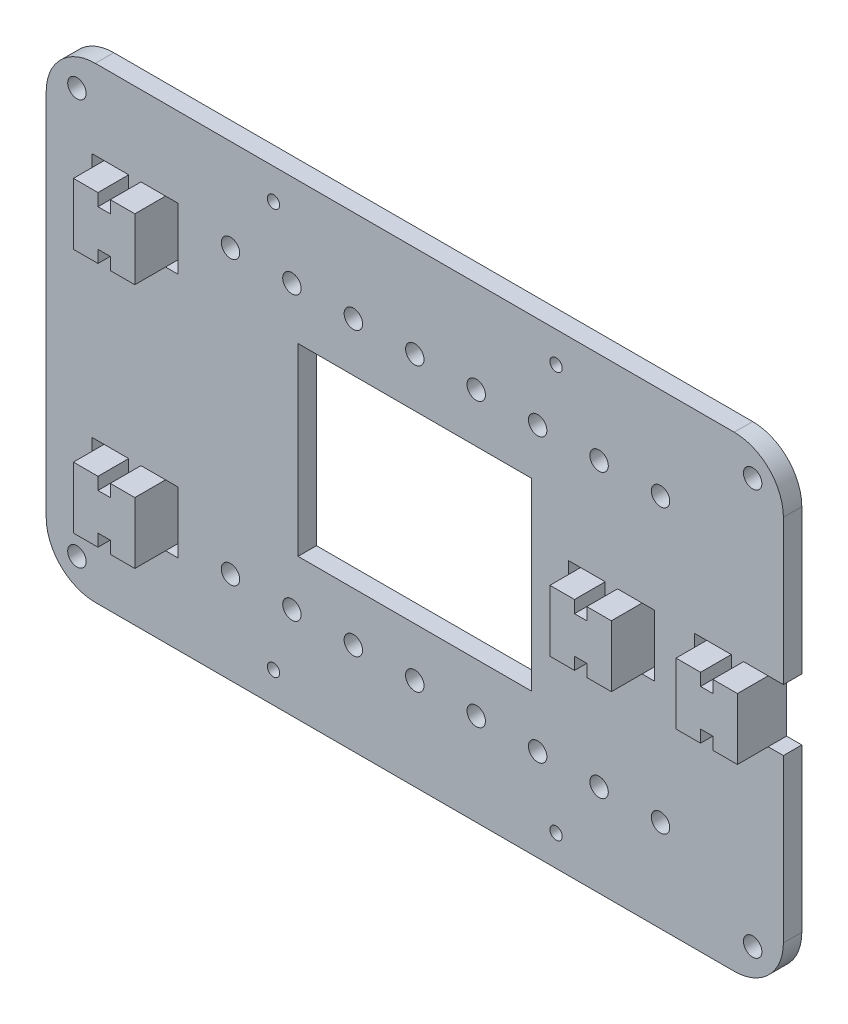
SolidWorks part; units mm, degrees
ref_plane "前视基准面" through (0, 0, 0) normal (0, 0, 1) x (1, 0, 0)
ref_plane "上视基准面" through (0, 0, 0) normal (0, 1, 0) x (1, 0, 0)
ref_plane "右视基准面" through (0, 0, 0) normal (1, 0, 0) x (0, 0, -1)
sketch "草图1" plane through (0, 0, 0) normal (0, 0, 1) x (1, 0, 0)
  line L0 (0, 0) -> (0, 3) construction
  line L1 (-5, 5) -> (-1, 5)
  line L2 (-5, 5) -> (-5, -5)
  line L3 (-5, -5) -> (-1, -5)
  line L4 (5, 5) -> (5, -5)
  line L5 (-5, 5) -> (5, -5) construction
  line L6 (-5, -5) -> (5, 5) construction
  line L7 (-1, 3) -> (1, 3)
  line L8 (-1, 3) -> (-1, 5)
  line L9 (1, 3) -> (1, 5)
  line L10 (0, 0) -> (2.3231, 0) construction
  line L11 (1, -3) -> (1, -5)
  line L12 (-1, -3) -> (1, -3)
  line L13 (-1, -3) -> (-1, -5)
  line L14 (1, 5) -> (5, 5)
  line L15 (1, -5) -> (5, -5)
  point P0 (0, 0)
  point P11 (0, 3)
  dimension "D1" = 10
  dimension "D2" = 10
  dimension "D3" = 2
  dimension "D4" = 2
sketch "草图2" plane through (0, 0, 0) normal (0, 0, 1) x (1, 0, 0)
  line L0 (0, -35) -> (0, 35) construction
  line L1 (-25, 35) -> (25, 35) construction
  line L2 (-25, 35) -> (-25, -35) construction
  line L3 (-25, -35) -> (25, -35) construction
  line L4 (25, 35) -> (25, -35) construction
  line L5 (57.5198, -3.5829) -> (57.5198, 6.4171) construction
  line L6 (-25, 0) -> (25, 0) construction
  line L7 (53.5198, -3.5829) -> (57.5198, -3.5829) construction
  line L8 (53.5198, 6.4171) -> (53.5198, 4.4171) construction
  line L9 (-60, 38) -> (60, 38)
  line L10 (-60, 38) -> (-60, -38)
  line L11 (-60, -38) -> (60, -38)
  line L12 (60, 38) -> (60, -38)
  line L13 (-60, 38) -> (60, -38) construction
  line L14 (-60, -38) -> (60, 38) construction
  line L15 (47.5198, -3.5829) -> (51.5198, -3.5829) construction
  line L16 (57.5198, 6.4171) -> (53.5198, 6.4171) construction
  line L17 (51.5198, -3.5829) -> (51.5198, -1.5829) construction
  line L18 (47.5198, 6.4171) -> (47.5198, -3.5829) construction
  line L19 (51.5198, -1.5829) -> (53.5198, -1.5829) construction
  line L20 (53.5198, -1.5829) -> (53.5198, -3.5829) construction
  line L21 (53.5198, 4.4171) -> (51.5198, 4.4171) construction
  line L22 (51.5198, 6.4171) -> (47.5198, 6.4171) construction
  line L23 (51.5198, 4.4171) -> (51.5198, 6.4171) construction
  line L24 (-5, -5) -> (-1, -5)
  line L25 (-5, 5) -> (-5, -5)
  line L26 (-1, 5) -> (-5, 5)
  line L27 (-1, 3) -> (-1, 5)
  line L28 (1, 3) -> (-1, 3)
  line L29 (1, 5) -> (1, 3)
  line L30 (5, 5) -> (1, 5)
  line L31 (5, -5) -> (5, 5)
  line L32 (1, -5) -> (5, -5)
  line L33 (1, -3) -> (1, -5)
  line L34 (-1, -3) -> (1, -3)
  line L35 (-1, -5) -> (-1, -3)
  line L36 (-5, -5) -> (-1, -5) construction
  line L37 (-5, 5) -> (-5, -5) construction
  line L38 (-1, 5) -> (-5, 5) construction
  line L39 (-1, 3) -> (-1, 5) construction
  line L40 (1, 3) -> (-1, 3) construction
  line L41 (1, 5) -> (1, 3) construction
  line L42 (5, 5) -> (1, 5) construction
  line L43 (5, -5) -> (5, 5) construction
  line L44 (1, -5) -> (5, -5) construction
  line L45 (1, -3) -> (1, -5) construction
  line L46 (-1, -3) -> (1, -3) construction
  line L47 (-1, -5) -> (-1, -3) construction
  line L48 (37, 6.4171) -> (33, 6.4171) construction
  line L49 (31, 6.4171) -> (27, 6.4171) construction
  line L50 (33, 6.4171) -> (33, 4.4171) construction
  line L51 (33, -1.5829) -> (33, -3.5829) construction
  line L52 (33, -3.5829) -> (37, -3.5829) construction
  line L53 (27, 6.4171) -> (27, -3.5829) construction
  line L54 (27, -3.5829) -> (31, -3.5829) construction
  line L55 (33, 4.4171) -> (31, 4.4171) construction
  line L56 (31, -3.5829) -> (31, -1.5829) construction
  line L57 (37, -3.5829) -> (37, 6.4171) construction
  line L58 (31, 4.4171) -> (31, 6.4171) construction
  line L59 (31, -1.5829) -> (33, -1.5829) construction
  line L60 (-46.5709, 17) -> (-44.5709, 17) construction
  line L61 (-46.5709, 23) -> (-46.5709, 25) construction
  line L62 (-46.5709, 25) -> (-50.5709, 25) construction
  line L63 (-44.5709, 17) -> (-44.5709, 15) construction
  line L64 (-40.5709, 15) -> (-40.5709, 25) construction
  line L65 (-44.5709, 15) -> (-40.5709, 15) construction
  line L66 (-44.5709, 23) -> (-46.5709, 23) construction
  line L67 (-44.5709, 25) -> (-44.5709, 23) construction
  line L68 (-46.5709, 15) -> (-46.5709, 17) construction
  line L69 (-50.5709, 15) -> (-46.5709, 15) construction
  line L70 (-40.5709, 25) -> (-44.5709, 25) construction
  line L71 (-50.5709, 25) -> (-50.5709, 15) construction
  line L72 (-46.5709, -15) -> (-50.5709, -15) construction
  line L73 (-46.5709, -25) -> (-46.5709, -23) construction
  line L74 (-40.5709, -15) -> (-44.5709, -15) construction
  line L75 (-50.5709, -15) -> (-50.5709, -25) construction
  line L76 (-44.5709, -25) -> (-40.5709, -25) construction
  line L77 (-46.5709, -23) -> (-44.5709, -23) construction
  line L78 (-44.5709, -15) -> (-44.5709, -17) construction
  line L79 (-44.5709, -17) -> (-46.5709, -17) construction
  line L80 (-46.5709, -17) -> (-46.5709, -15) construction
  line L81 (-44.5709, -23) -> (-44.5709, -25) construction
  line L82 (-50.5709, -25) -> (-46.5709, -25) construction
  line L83 (-40.5709, -25) -> (-40.5709, -15) construction
  circle A0 centre (-23, 33) radius 1
  circle A1 centre (23, 33) radius 1
  circle A2 centre (23, -33) radius 1
  circle A3 centre (-23, -33) radius 1
  point P0 (0, 0)
  point P11 (0, 0)
  point P14 (0, 0)
  point P20 (0, 0)
  point P61 (27, 1.4171)
  point P74 (0, 0)
  point P87 (-48.5709, -15)
  dimension "D3" = 2
  dimension "D4" = 2
  dimension "D5" = 2
  dimension "D1" = 50
  dimension "D2" = 70
  dimension "D6" = 76
  dimension "D7" = 120
  dimension "D9" = 2
  dimension "D10" = 15
  dimension "D11" = 15
  dimension "D8" = 0
extrude "凸台-拉伸2" add sketch "草图2" along normal blind 3
sketch "草图3" plane through (0, 0, 3) normal (0, 0, 1) x (1, 0, 0)
  line L1 (-19, 15) -> (19, 15)
  line L2 (-19, 15) -> (-19, -15)
  line L3 (-19, -15) -> (19, -15)
  line L4 (19, 15) -> (19, -15)
  line L5 (-19, 15) -> (19, -15) construction
  line L6 (-19, -15) -> (19, 15) construction
  circle A0 centre (-23, 33) radius 1 construction
  point P0 (0, 0)
  dimension "D1" = 30
  dimension "D2" = 4
extrude "切除-拉伸1" cut sketch "草图3" against normal blind 3
sketch "草图6" plane through (0, 0, 3) normal (0, 0, 1) x (1, 0, 0)
  line L0 (-50.5709, 25) -> (-50.5709, 15)
  line L1 (-50.5709, 15) -> (-46.5709, 15)
  line L2 (-46.5709, 15) -> (-46.5709, 17)
  line L3 (-46.5709, 17) -> (-44.5709, 17)
  line L4 (-44.5709, 17) -> (-44.5709, 15)
  line L5 (-44.5709, 15) -> (-40.5709, 15)
  line L6 (-40.5709, 15) -> (-40.5709, 25)
  line L7 (-40.5709, 25) -> (-44.5709, 25)
  line L8 (-44.5709, 25) -> (-44.5709, 23)
  line L9 (-44.5709, 23) -> (-46.5709, 23)
  line L10 (-46.5709, 23) -> (-46.5709, 25)
  line L11 (-46.5709, 25) -> (-50.5709, 25)
  line L12 (-50.5709, -15) -> (-50.5709, -25)
  line L13 (-50.5709, -25) -> (-46.5709, -25)
  line L14 (-44.5709, -23) -> (-44.5709, -25)
  line L15 (-46.5709, -25) -> (-46.5709, -23)
  line L16 (-40.5709, -25) -> (-40.5709, -15)
  line L17 (-44.5709, -15) -> (-44.5709, -17)
  line L18 (-40.5709, -15) -> (-44.5709, -15)
  line L19 (-44.5709, -25) -> (-40.5709, -25)
  line L20 (-46.5709, -17) -> (-46.5709, -15)
  line L21 (-46.5709, -15) -> (-50.5709, -15)
  line L22 (-44.5709, -17) -> (-46.5709, -17)
  line L23 (-46.5709, -23) -> (-44.5709, -23)
  line L24 (31, -1.5829) -> (33, -1.5829)
  line L25 (37, 6.4171) -> (33, 6.4171)
  line L26 (31, 6.4171) -> (27, 6.4171)
  line L27 (27, -3.5829) -> (31, -3.5829)
  line L28 (37, -3.5829) -> (37, 6.4171)
  line L29 (33, -1.5829) -> (33, -3.5829)
  line L30 (33, 4.4171) -> (31, 4.4171)
  line L31 (31, -3.5829) -> (31, -1.5829)
  line L32 (31, 4.4171) -> (31, 6.4171)
  line L33 (33, 6.4171) -> (33, 4.4171)
  line L34 (27, 6.4171) -> (27, -3.5829)
  line L35 (33, -3.5829) -> (37, -3.5829)
  line L36 (53.5198, 6.4171) -> (53.5198, 4.4171)
  line L37 (51.5198, 6.4171) -> (47.5198, 6.4171)
  line L38 (57.5198, 6.4171) -> (53.5198, 6.4171)
  line L39 (53.5198, 4.4171) -> (51.5198, 4.4171)
  line L40 (53.5198, -1.5829) -> (53.5198, -3.5829)
  line L41 (51.5198, 4.4171) -> (51.5198, 6.4171)
  line L42 (53.5198, -3.5829) -> (57.5198, -3.5829)
  line L43 (57.5198, -3.5829) -> (57.5198, 6.4171)
  line L44 (47.5198, 6.4171) -> (47.5198, -3.5829)
  line L45 (51.5198, -1.5829) -> (53.5198, -1.5829)
  line L46 (47.5198, -3.5829) -> (51.5198, -3.5829)
  line L47 (51.5198, -3.5829) -> (51.5198, -1.5829)
extrude "凸台-拉伸3" add sketch "草图6" along normal blind 5
sketch "草图7" plane through (0, 0, 3) normal (0, 0, 1) x (1, 0, 0)
  line L0 (-50.5709, 25) -> (-52.5709, 25)
  line L1 (-52.5709, 25) -> (-52.5709, 15)
  line L2 (-52.5709, 15) -> (-50.5709, 15)
  line L3 (-40.5709, 25) -> (-38.5709, 25)
  line L4 (-38.5709, 25) -> (-38.5709, 15)
  line L5 (-38.5709, 15) -> (-40.5709, 15)
  line L6 (-50.5709, 25) -> (-50.5709, 15)
  line L7 (-40.5709, 25) -> (-40.5709, 15)
  line L8 (-50.5709, -15) -> (-50.5709, -25)
  line L9 (-52.5709, -25) -> (-50.5709, -25)
  line L10 (-52.5709, -15) -> (-52.5709, -25)
  line L11 (-50.5709, -15) -> (-52.5709, -15)
  line L12 (-40.5709, -15) -> (-40.5709, -25)
  line L13 (-40.5709, -25) -> (-38.5709, -25)
  line L14 (-38.5709, -15) -> (-40.5709, -15)
  line L15 (-38.5709, -15) -> (-38.5709, -25)
  line L16 (25, 6.4171) -> (25, -3.5829)
  line L17 (27, 6.4171) -> (27, -3.5829)
  line L18 (39, -3.5829) -> (37, -3.5829)
  line L19 (37, 6.4171) -> (39, 6.4171)
  line L20 (27, 6.4171) -> (25, 6.4171)
  line L21 (39, 6.4171) -> (39, -3.5829)
  line L22 (25, -3.5829) -> (27, -3.5829)
  line L23 (37, 6.4171) -> (37, -3.5829)
  line L24 (47.5198, 6.4171) -> (47.5198, -3.5829)
  line L25 (45.5198, 6.4171) -> (45.5198, -3.5829)
  line L26 (57.5198, 6.4171) -> (57.5198, -3.5829)
  line L27 (57.5198, 6.4171) -> (60.5198, 6.4171)
  line L28 (47.5198, 6.4171) -> (45.5198, 6.4171)
  line L29 (45.5198, -3.5829) -> (47.5198, -3.5829)
  line L30 (60.5198, -3.5829) -> (57.5198, -3.5829)
  line L31 (60.5198, 6.4171) -> (60.5198, -3.5829)
  dimension "D1" = 2
  dimension "D2" = 2
  dimension "D3" = 3
extrude "切除-拉伸2" cut sketch "草图7" against normal blind 5
sketch "草图9" plane through (0, 0, 3) normal (0, 0, 1) x (1, 0, 0)
  line L0 (0, -35) -> (0, 35) construction
  line L1 (-60, -38) -> (60, -38) construction
  line L2 (-60, -23) -> (60, -23) construction
  line L3 (60, 38) -> (60, -38) construction
  line L4 (0, -23) -> (0, 23.4281) construction
  line L5 (-21.8335, 0) -> (21.8335, 0) construction
  line L6 (-25, 0) -> (25, 0) construction
  line L7 (0, 23) -> (0, -23.4281) construction
  line L8 (-60, 23) -> (60, 23) construction
  circle A0 centre (0, -23) radius 1.5
  circle A1 centre (10, -23) radius 1.5
  circle A2 centre (20, -23) radius 1.5
  circle A3 centre (30, -23) radius 1.5
  circle A4 centre (40, -23) radius 1.5
  circle A6 centre (-30, -23) radius 1.5
  circle A7 centre (-20, -23) radius 1.5
  circle A8 centre (-10, -23) radius 1.5
  circle A9 centre (-10, 23) radius 1.5
  circle A10 centre (-20, 23) radius 1.5
  circle A11 centre (-30, 23) radius 1.5
  circle A12 centre (40, 23) radius 1.5
  circle A13 centre (30, 23) radius 1.5
  circle A14 centre (20, 23) radius 1.5
  circle A15 centre (10, 23) radius 1.5
  circle A16 centre (0, 23) radius 1.5
  point P6 (0, -38)
  point P12 (0, -23)
  point P33 (0, 0)
  dimension "D1" = 3
  dimension "D2" = 15
  dimension "D3" = 10
  dimension "D4" = 10
  dimension "D5" = 10
  dimension "D6" = 10
extrude "切除-拉伸3" cut sketch "草图9" against normal blind 5
fillet "圆角1" radius 8 4 edges at (60, 38, 1.5) (60, -38, 1.5) (-60, -38, 1.5) (-60, 38, 1.5)
sketch "草图10" plane through (0, 0, 3) normal (0, 0, 1) x (1, 0, 0)
  line L0 (52, 38) -> (-52, 38) construction
  line L1 (-60, 30) -> (-60, -30) construction
  line L2 (0, -29.4925) -> (0, 29.4925) construction
  line L3 (-39, 0) -> (39, 0) construction
  line L4 (39, -3.5829) -> (39, 6.4171) construction
  circle A0 centre (-55, 33) radius 1.5
  circle A4 centre (55, 33) radius 1.5
  circle A5 centre (55, -33) radius 1.5
  circle A6 centre (-55, -33) radius 1.5
  point P16 (0, 0)
  point P22 (0, 0)
  dimension "D1" = 3
  dimension "D2" = 5
  dimension "D3" = 5
extrude "切除-拉伸4" cut sketch "草图10" against normal blind 5
